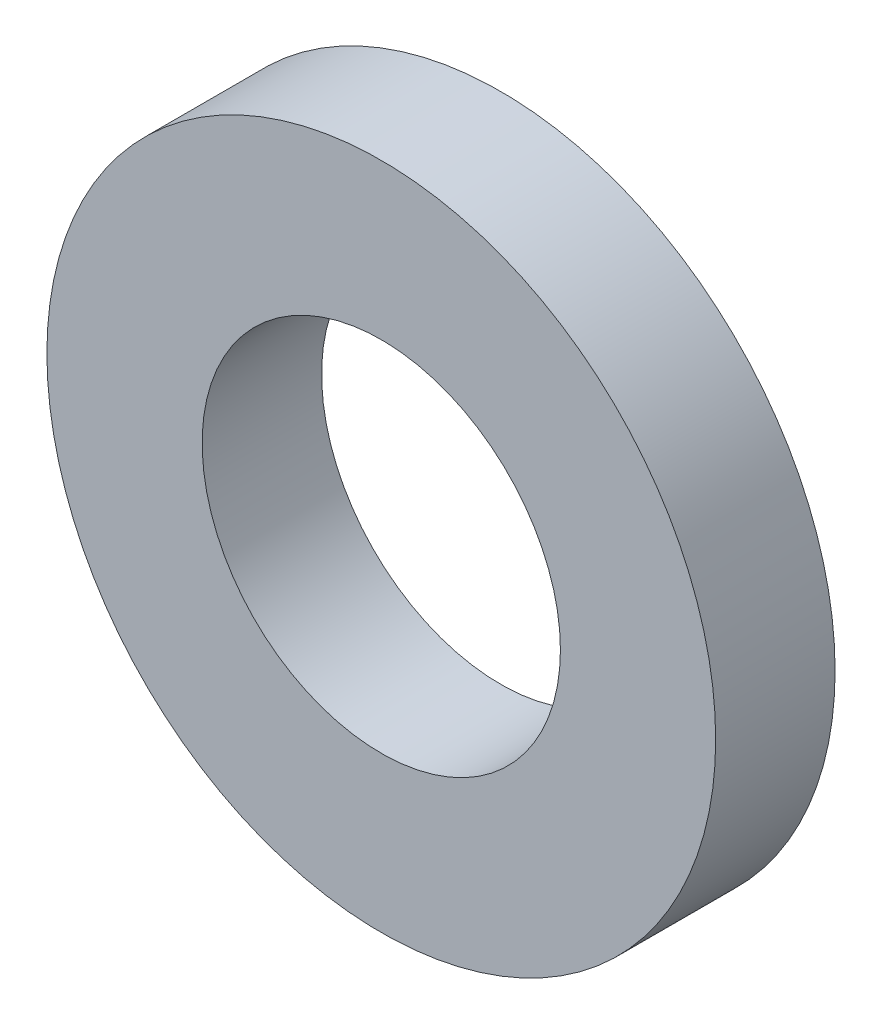
SolidWorks part; units mm, degrees
ref_plane "Front Plane" through (0, 0, 0) normal (0, 0, 1) x (1, 0, 0)
ref_plane "Top Plane" through (0, 0, 0) normal (0, 1, 0) x (1, 0, 0)
ref_plane "Right Plane" through (0, 0, 0) normal (1, 0, 0) x (0, 0, -1)
sketch "Sketch1" plane through (0, 0, 0) normal (0, 0, 1) x (1, 0, 0)
  circle A0 centre (0, 0) radius 14
  circle A1 centre (0, 0) radius 7.5
  dimension "D1" = 28
  dimension "D2" = 15
extrude "Boss-Extrude1" add sketch "Sketch1" along normal blind 5
